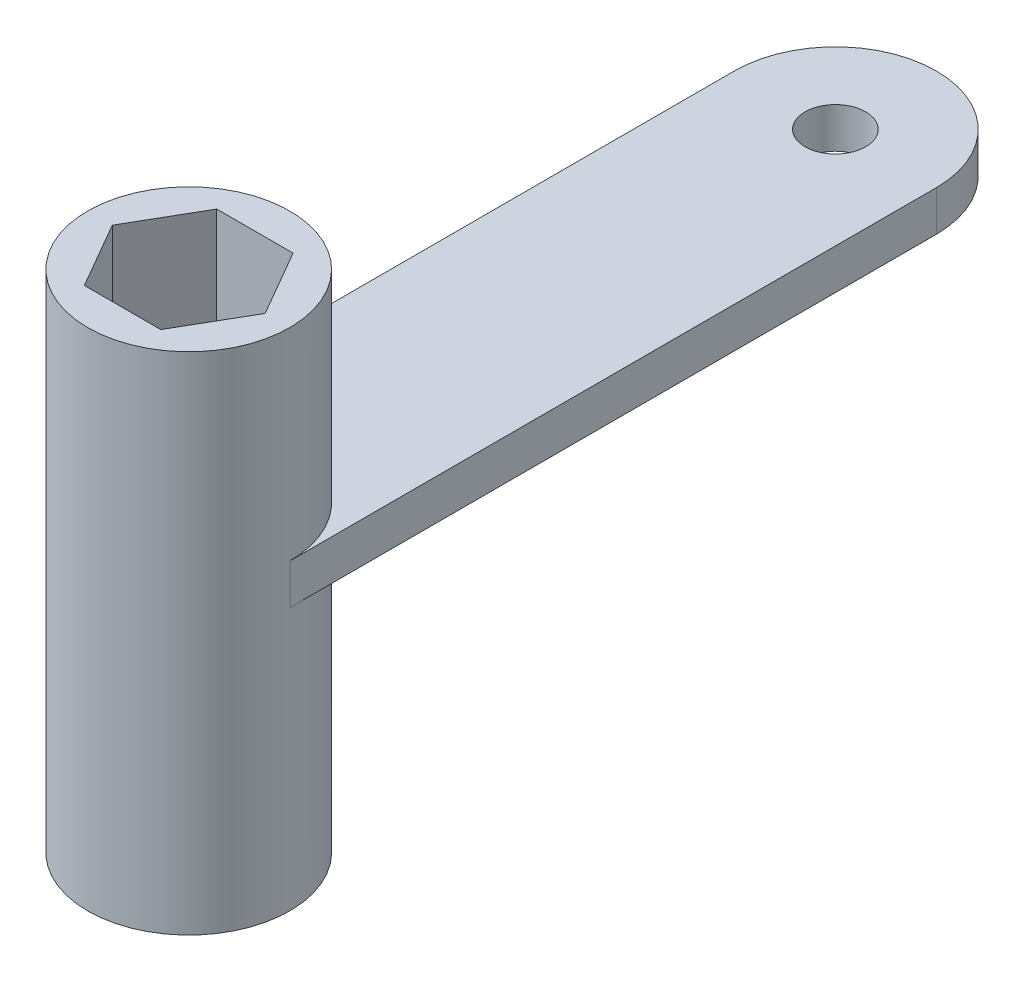
SolidWorks part; units mm, degrees
ref_plane "前视基准面" through (0, 0, 0) normal (0, 0, 1) x (1, 0, 0)
ref_plane "上视基准面" through (0, 0, 0) normal (0, 1, 0) x (1, 0, 0)
ref_plane "右视基准面" through (0, 0, 0) normal (1, 0, 0) x (0, 0, -1)
sketch "草图1" plane through (0, 0, 0) normal (0, 1, 0) x (1, 0, 0)
  line L0 (0, -16) -> (0, 16) construction
  line L1 (-5, -16) -> (-5, 16)
  line L2 (5, -16) -> (5, 16)
  line L3 (-1000, 0) -> (49000, 0) construction
  line L5 (1.8908, -12.725) -> (-1.8908, -12.725)
  line L6 (-1.8908, -12.725) -> (-3.7816, -16)
  line L7 (-3.7816, -16) -> (-1.8908, -19.275)
  line L8 (-1.8908, -19.275) -> (1.8908, -19.275)
  line L9 (1.8908, -19.275) -> (3.7816, -16)
  line L10 (3.7816, -16) -> (1.8908, -12.725)
  arc A0 (-5, -16) -> (5, -16) centre (0, -16) ccw
  arc A1 (5, 16) -> (-5, 16) centre (0, 16) ccw
  circle A2 centre (0, 16) radius 1.5
  circle A4 centre (0, -16) radius 3.275 construction
  point P3 (0, 0)
  dimension "D3" = 3
  dimension "D4" = 6.55
  dimension "D1" = 32
  dimension "D2" = 10
extrude "凸台-拉伸1" add sketch "草图1" along normal blind 2
sketch "草图2" plane through (0, 2, 0) normal (0, 1, 0) x (1, 0, 0)
  line L0 (3.7816, -16) -> (1.8908, -12.725) construction
  line L1 (1.8908, -19.275) -> (3.7816, -16) construction
  line L2 (-1.8908, -19.275) -> (1.8908, -19.275) construction
  line L3 (-3.7816, -16) -> (-1.8908, -19.275) construction
  line L4 (-1.8908, -12.725) -> (-3.7816, -16) construction
  line L5 (1.8908, -12.725) -> (-1.8908, -12.725) construction
  line L6 (3.7816, -16) -> (1.8908, -12.725)
  line L7 (1.8908, -19.275) -> (3.7816, -16)
  line L8 (-1.8908, -19.275) -> (1.8908, -19.275)
  line L9 (-3.7816, -16) -> (-1.8908, -19.275)
  line L10 (-1.8908, -12.725) -> (-3.7816, -16)
  line L11 (1.8908, -12.725) -> (-1.8908, -12.725)
  circle A0 centre (0, -16) radius 5
extrude "凸台-拉伸2" add sketch "草图2" along normal blind 10
sketch "草图4" plane through (0, 12, 0) normal (0, 1, 0) x (1, 0, 0)
  line L0 (-1.8908, -12.725) -> (1.8908, -12.725)
  line L1 (1.8908, -12.725) -> (3.7816, -16)
  line L2 (3.7816, -16) -> (1.8908, -19.275)
  line L3 (1.8908, -19.275) -> (-1.8908, -19.275)
  line L4 (-1.8908, -19.275) -> (-3.7816, -16)
  line L5 (-3.7816, -16) -> (-1.8908, -12.725)
  circle A2 centre (0, -16) radius 5
  circle A3 centre (0, -16) radius 5
  dimension "D1" = 0
extrude "凸台-拉伸3" add sketch "草图4" against normal blind 25
sketch "草图5" plane through (0, -13, 0) normal (0, -1, 0) x (1, 0, 0)
  line L0 (-3.7816, 16) -> (-1.8908, 12.725)
  line L1 (-1.8908, 12.725) -> (1.8908, 12.725)
  line L2 (1.8908, 12.725) -> (3.7816, 16)
  line L3 (3.7816, 16) -> (1.8908, 19.275)
  line L4 (1.8908, 19.275) -> (-1.8908, 19.275)
  line L5 (-1.8908, 19.275) -> (-3.7816, 16)
  circle A1 centre (0, 16) radius 5
  circle A2 centre (0, 16) radius 5
  line M2 (1.8908, 12.725) -> (-1.8908, 12.725)
  line M3 (-1.8908, 12.725) -> (-3.7816, 16)
  line M4 (-3.7816, 16) -> (-1.8908, 19.275)
  line M5 (-1.8908, 19.275) -> (1.8908, 19.275)
  line M6 (1.8908, 19.275) -> (3.7816, 16)
  line M7 (3.7816, 16) -> (1.8908, 12.725)
  dimension "D1" = 0
extrude "凸台-拉伸4" add sketch "草图5" against normal blind 7.8 contours M2 M7 M6 M5 M4 M3
sketch "草图6" plane through (0, -13, 0) normal (0, -1, 0) x (1, 0, 0)
  circle A0 centre (0, 16) radius 1.6
  dimension "D1" = 3.2
extrude "凸台-拉伸5" add sketch "草图6" against normal blind 5 from surface at -7.8 starting at face at (0, -5.2, 16)
